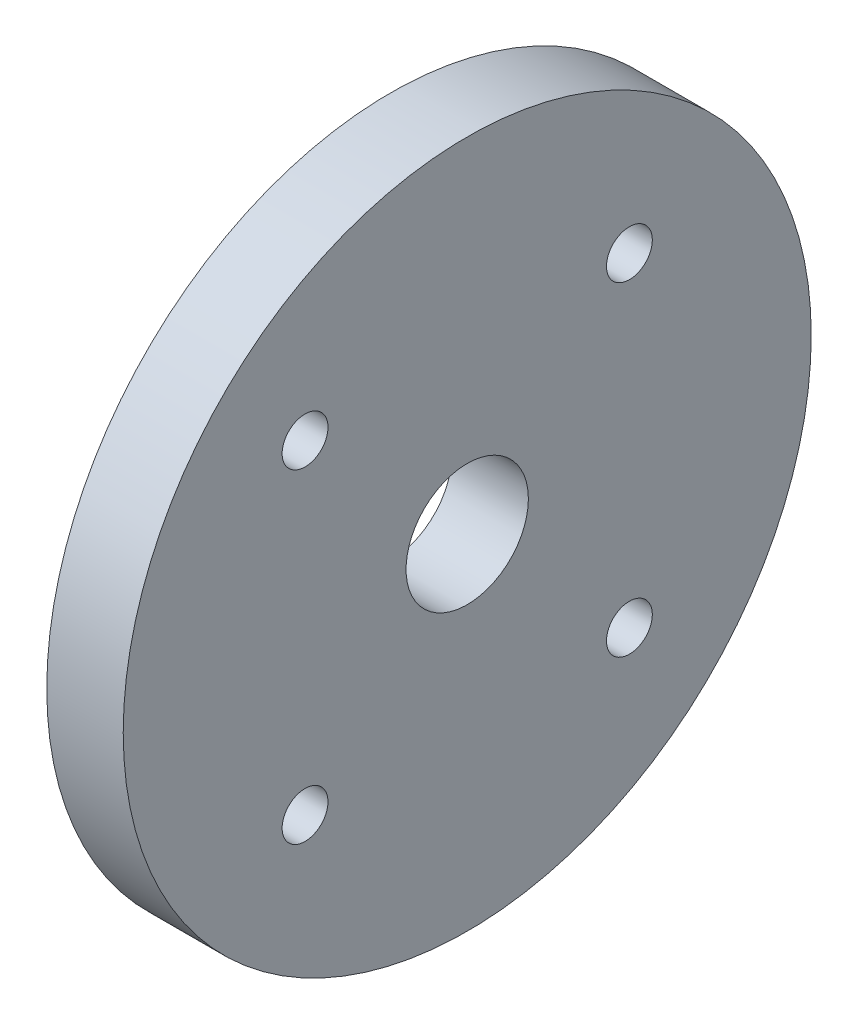
SolidWorks part; units mm, degrees
material "Alloy Steel"
ref_plane "Front Plane" through (0, 0, 0) normal (0, 0, 1) x (1, 0, 0)
ref_plane "Top Plane" through (0, 0, 0) normal (0, 1, 0) x (1, 0, 0)
ref_plane "Right Plane" through (0, 0, 0) normal (1, 0, 0) x (0, 0, -1)
sketch "Sketch1" plane through (0, 0, 0) normal (1, 0, 0) x (0, 0, -1)
  line L0 (0, 22.5) -> (0, -22.5) construction
  line L1 (-15.9099, 15.9099) -> (15.9099, -15.9099) construction
  line L2 (-22.5, 0) -> (22.5, 0) construction
  circle A0 centre (0, 0) radius 22.5
  circle A1 centre (0, 0) radius 4
  circle A2 centre (-10.6066, 10.6066) radius 1.5
  circle A3 centre (-10.6066, -10.6066) radius 1.5
  circle A4 centre (10.6066, -10.6066) radius 1.5
  circle A5 centre (10.6066, 10.6066) radius 1.5
  point P12 (0, 0)
  point P13 (0, 0)
  dimension "D1" = 45
  dimension "D2" = 8
  dimension "D4" = 3
  dimension "D3" = 45
  dimension "D5" = 15
extrude "Boss-Extrude1" add sketch "Sketch1" along normal blind 5
